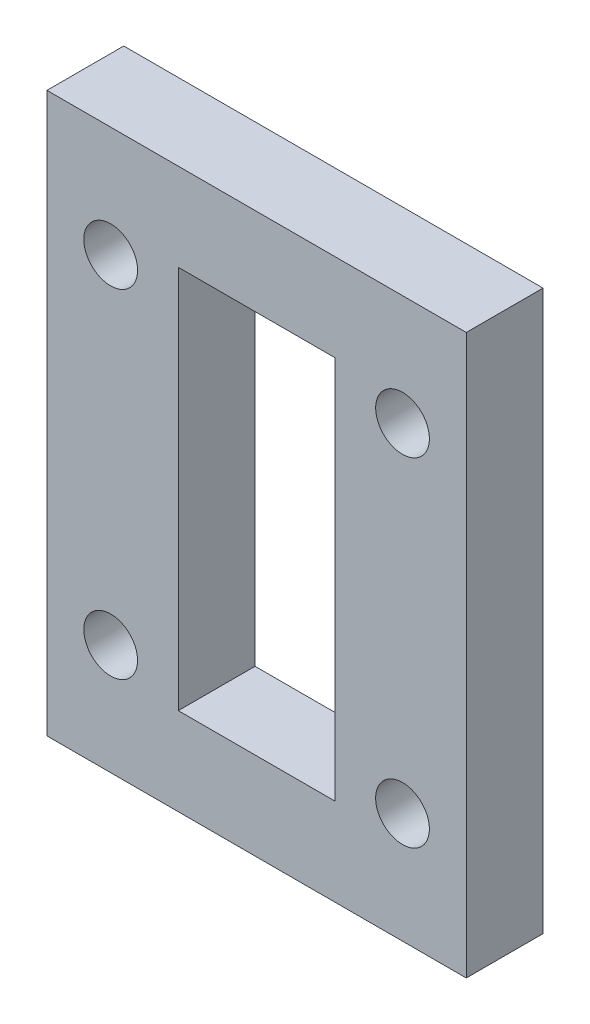
SolidWorks part; units mm, degrees
ref_plane "Front Plane" through (0, 0, 0) normal (0, 0, 1) x (1, 0, 0)
ref_plane "Top Plane" through (0, 0, 0) normal (0, 1, 0) x (1, 0, 0)
ref_plane "Right Plane" through (0, 0, 0) normal (1, 0, 0) x (0, 0, -1)
sketch "Sketch1" plane through (0, 0, 0) normal (0, 0, 1) x (1, 0, 0)
  line L1 (-13.65, -18.2) -> (13.65, -18.2)
  line L2 (-13.65, -18.2) -> (-13.65, 18.2)
  line L3 (-13.65, 18.2) -> (13.65, 18.2)
  line L4 (13.65, -18.2) -> (13.65, 18.2)
  line L5 (-13.65, -18.2) -> (13.65, 18.2) construction
  line L6 (-13.65, 18.2) -> (13.65, -18.2) construction
  line L7 (-5.1, -12.5) -> (5.1, -12.5)
  line L8 (-5.1, -12.5) -> (-5.1, 12.5)
  line L9 (-5.1, 12.5) -> (5.1, 12.5)
  line L10 (5.1, -12.5) -> (5.1, 12.5)
  line L11 (-5.1, -12.5) -> (5.1, 12.5) construction
  line L12 (-5.1, 12.5) -> (5.1, -12.5) construction
  point P0 (0, 0)
  point P6 (0, 0)
  dimension "D1" = 27.3
  dimension "D2" = 36.4
  dimension "D3" = 25
  dimension "D4" = 10.2
extrude "Boss-Extrude1" add sketch "Sketch1" along normal blind 5
sketch "Sketch2" plane through (0, 0, 5) normal (0, 0, 1) x (1, 0, 0)
  line L1 (0, 18.2) -> (0, -18.2) construction
  line L6 (13.65, 18.2) -> (-13.65, 18.2) construction
  line L7 (-13.65, -18.2) -> (13.65, -18.2) construction
  line L8 (-13.65, 0) -> (13.65, 0) construction
  line L9 (-13.65, 18.2) -> (-13.65, -18.2) construction
  line L10 (13.65, -18.2) -> (13.65, 18.2) construction
  circle A0 centre (-9.5, 11) radius 1.75
  circle A1 centre (9.5, 11) radius 1.75
  circle A2 centre (-9.5, -11) radius 1.75
  circle A3 centre (9.5, -11) radius 1.75
  dimension "D1" = 3.5
  dimension "D2" = 11
  dimension "D3" = 9.5
extrude "Cut-Extrude1" cut sketch "Sketch2" against normal up to surface (5 mm away) up to face at (0, 0, 0)
